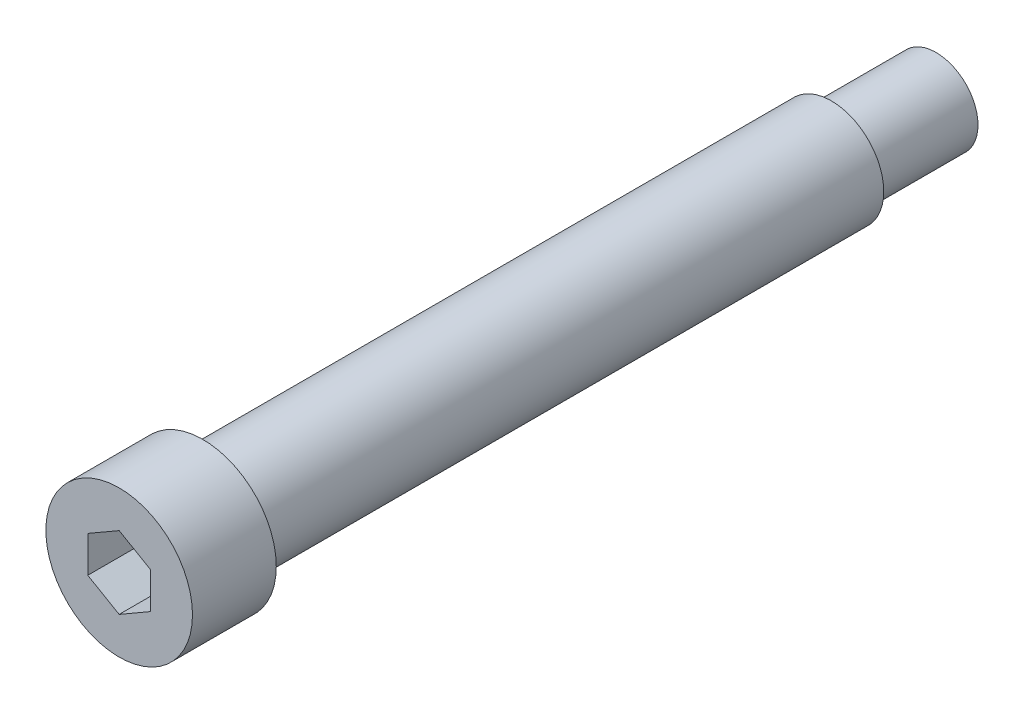
SolidWorks part; units mm, degrees
ref_plane "Спереди" through (0, 0, 0) normal (0, 0, 1) x (1, 0, 0)
ref_plane "Сверху" through (0, 0, 0) normal (0, 1, 0) x (1, 0, 0)
ref_plane "Справа" through (0, 0, 0) normal (1, 0, 0) x (0, 0, -1)
sketch "Эскиз1" plane through (0, 0, 0) normal (0, 0, 1) x (1, 0, 0)
  circle A0 centre (0, 0) radius 2
  dimension "D1" = 4
extrude "Бобышка-Вытянуть1" add sketch "Эскиз1" along normal blind 5
sketch "Эскиз2" plane through (0, 0, 5) normal (0, 0, 1) x (1, 0, 0)
  circle A0 centre (0, 0) radius 2.5
  dimension "D1" = 5
extrude "Бобышка-Вытянуть2" add sketch "Эскиз2" along normal blind 30
sketch "Эскиз3" plane through (0, 0, 35) normal (0, 0, 1) x (1, 0, 0)
  circle A0 centre (0, 0) radius 3.5
  dimension "D1" = 7
extrude "Бобышка-Вытянуть3" add sketch "Эскиз3" along normal blind 4
sketch "Эскиз4" plane through (0, 0, 39) normal (0, 0, 1) x (1, 0, 0)
  line L1 (1.5, 0.866) -> (0, 1.7321)
  line L2 (0, 1.7321) -> (-1.5, 0.866)
  line L3 (-1.5, 0.866) -> (-1.5, -0.866)
  line L4 (-1.5, -0.866) -> (0, -1.7321)
  line L5 (0, -1.7321) -> (1.5, -0.866)
  line L6 (1.5, -0.866) -> (1.5, 0.866)
  circle A0 centre (0, 0) radius 1.5 construction
  dimension "D1" = 3
extrude "Вырез-Вытянуть1" cut sketch "Эскиз4" against normal blind 3
